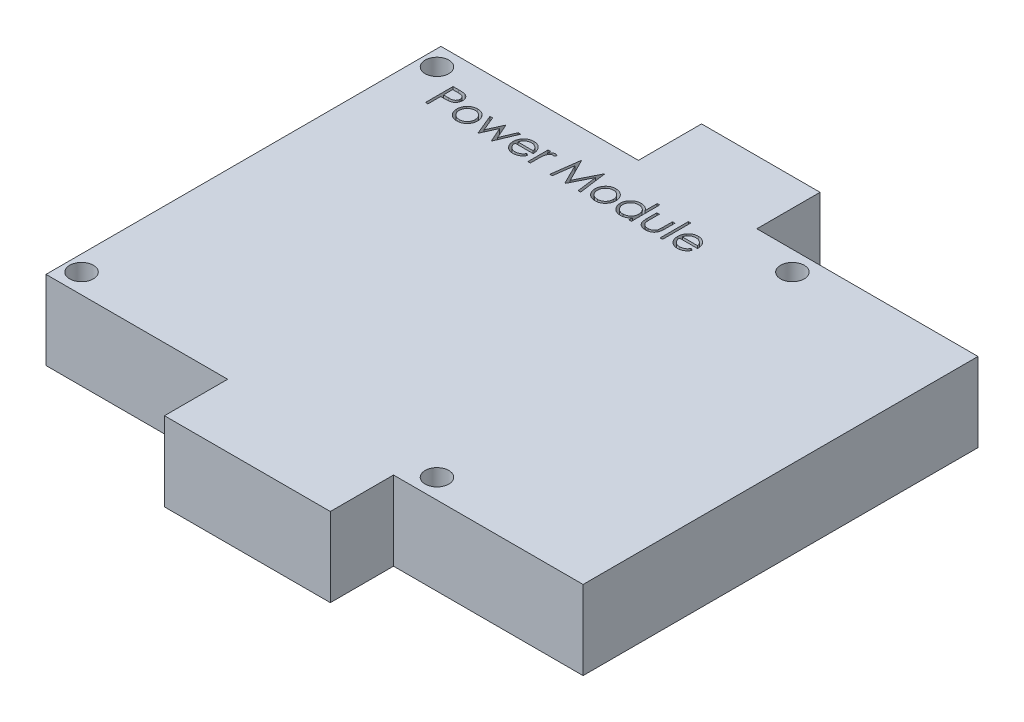
SolidWorks part; units mm, degrees
material "Manual Density from Real Component Mass Power Module"
ref_plane "Piano frontale" through (0, 0, 0) normal (0, 0, 1) x (1, 0, 0)
ref_plane "Piano superiore" through (0, 0, 0) normal (0, 1, 0) x (1, 0, 0)
ref_plane "Piano destro" through (0, 0, 0) normal (1, 0, 0) x (0, 0, -1)
sketch "Schizzo1" plane through (0, 0, 0) normal (0, 1, 0) x (1, 0, 0)
  line L1 (-34, -25) -> (34, -25)
  line L2 (-34, -25) -> (-34, 25)
  line L3 (-34, 25) -> (34, 25)
  line L4 (34, -25) -> (34, 25)
  line L5 (-34, -25) -> (34, 25) construction
  line L6 (-34, 25) -> (34, -25) construction
  point P0 (0, 0)
  dimension "D1" = 68
  dimension "D2" = 50
extrude "Estrusione-Estrusione1" add sketch "Schizzo1" along normal blind 10
sketch "Schizzo2" plane through (0, 10, 0) normal (0, 1, 0) x (1, 0, 0)
  text T0 "Power Module"
extrude "Taglio-Estrusione1" cut sketch "Schizzo2" against normal blind 3
sketch "Schizzo6" plane through (0, 0, 25) normal (0, 0, 1) x (1, 0, 0)
  line L0 (27.5, 0) -> (-27.5, 0) construction
  line L1 (-11, 0) -> (10, 0)
  line L2 (-11, 0) -> (-11, 10)
  line L3 (-11, 10) -> (10, 10)
  line L4 (10, 0) -> (10, 10)
  line L5 (-34, 10) -> (34, 10) construction
  line L7 (-34, 10) -> (-34, 0) construction
  line L8 (34, 10) -> (34, 0) construction
  dimension "D1" = 23
  dimension "D2" = 24
extrude "Estrusione-Estrusione2" add sketch "Schizzo6" along normal blind 8
sketch "Schizzo7" plane through (0, 0, -25) normal (0, 0, -1) x (-1, 0, 0)
  line L0 (-34, 0) -> (34, 0) construction
  line L1 (-6, 0) -> (9, 0)
  line L2 (-6, 0) -> (-6, 10)
  line L3 (-6, 10) -> (9, 10)
  line L4 (9, 0) -> (9, 10)
  line L5 (-34, 10) -> (34, 10) construction
  dimension "D1" = 25
  dimension "D2" = 28
extrude "Estrusione-Estrusione3" add sketch "Schizzo7" along normal blind 8
sketch "Schizzo3" plane through (0, 10, 0) normal (0, 1, 0) x (1, 0, 0)
  line L0 (34, -25) -> (34, 25) construction
  line L1 (-34, -25) -> (-11, -25) construction
  circle A0 centre (13, -22.5) radius 1.5
  dimension "D1" = 3
  dimension "D2" = 21
  dimension "D3" = 2.5
extrude "Taglio-Estrusione2" cut sketch "Schizzo3" against normal through all
sketch "Schizzo4" plane through (0, 10, 0) normal (0, 1, 0) x (1, 0, 0)
  line L0 (-34, 25) -> (-34, -25) construction
  line L1 (-34, -25) -> (-11, -25) construction
  circle A0 centre (-32, -22.5) radius 1.5
  dimension "D1" = 3
  dimension "D2" = 2
  dimension "D3" = 2.5
extrude "Taglio-Estrusione3" cut sketch "Schizzo4" against normal through all
mirror "Specchia2" about plane through (0, 0, 0) normal (0, 0, 1) of "Taglio-Estrusione3", "Taglio-Estrusione2"
